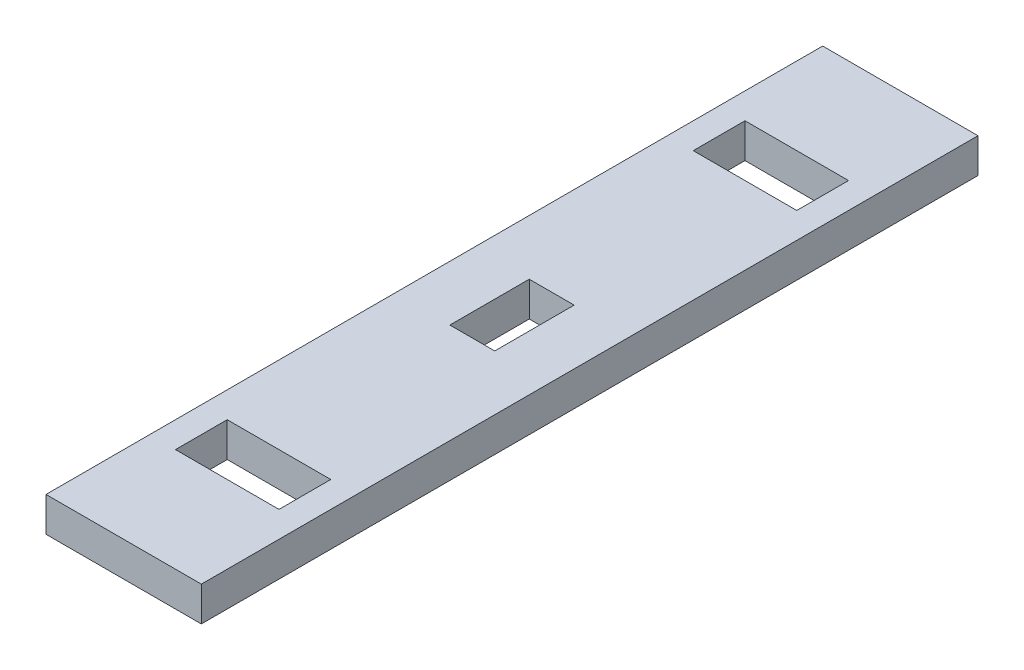
SolidWorks part; units mm, degrees
ref_plane "Plan de face" through (0, 0, 0) normal (0, 0, 1) x (1, 0, 0)
ref_plane "Plan de dessus" through (0, 0, 0) normal (0, 1, 0) x (1, 0, 0)
ref_plane "Plan de droite" through (0, 0, 0) normal (1, 0, 0) x (0, 0, -1)
sketch "Esquisse1" plane through (0, 0, 0) normal (0, 1, 0) x (1, 0, 0)
  line L0 (3.409, -1.8775) -> (3.409, 4.1225) construction
  line L1 (-1.091, 43.1225) -> (7.909, 43.1225)
  line L2 (-1.091, 43.1225) -> (-1.091, -1.8775)
  line L3 (-1.091, -1.8775) -> (7.909, -1.8775)
  line L4 (7.909, 43.1225) -> (7.909, -1.8775)
  line L5 (0.409, 4.1225) -> (6.409, 4.1225)
  line L6 (0.409, 4.1225) -> (0.409, 7.1225)
  line L7 (0.409, 7.1225) -> (6.409, 7.1225)
  line L8 (6.409, 4.1225) -> (6.409, 7.1225)
  line L9 (-1.091, 20.6225) -> (7.909, 20.6225) construction
  line L10 (0.409, 34.1225) -> (6.409, 34.1225)
  line L11 (6.409, 37.1225) -> (6.409, 34.1225)
  line L12 (0.409, 37.1225) -> (6.409, 37.1225)
  line L13 (0.409, 37.1225) -> (0.409, 34.1225)
  dimension "D1" = 45
  dimension "D2" = 9
  dimension "D3" = 6
  dimension "D4" = 6
  dimension "D5" = 3
extrude "Boss.-Extru.1" add sketch "Esquisse1" along normal blind 2 contours L4 L1 L2 L3 L13 L12 L11 L10 L8 L5 L6 L7
sketch "Esquisse2" plane through (0, 0, 0) normal (0, -1, 0) x (1, 0, 0)
  line L0 (-1.091, -20.6225) -> (7.909, -20.6225) construction
  line L1 (-1.091, -43.1225) -> (-1.091, 1.8775) construction
  line L2 (7.909, -43.1225) -> (7.909, 1.8775) construction
  line L4 (4.709, -22.9225) -> (2.109, -22.9225)
  line L5 (4.709, -22.9225) -> (4.709, -18.3225)
  line L6 (4.709, -18.3225) -> (2.109, -18.3225)
  line L7 (2.109, -22.9225) -> (2.109, -18.3225)
  line L8 (4.709, -22.9225) -> (2.109, -18.3225) construction
  line L9 (4.709, -18.3225) -> (2.109, -22.9225) construction
  point P6 (3.409, -20.6225)
  point P11 (3.409, -20.6225)
  dimension "D1" = 4.6
  dimension "D2" = 2.6
extrude "Enlèv. mat.-Extru.1" cut sketch "Esquisse2" along normal through all and the other way through all contours L7 L4 L5 L6
